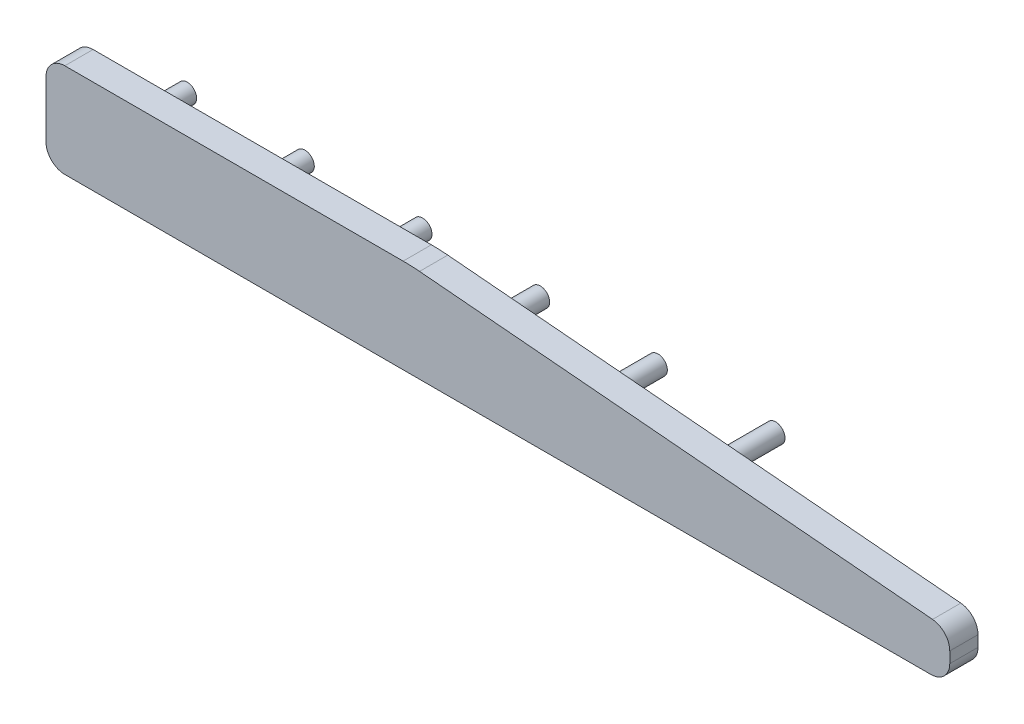
SolidWorks part; units mm, degrees
ref_plane "Front Plane" through (0, 0, 0) normal (0, 0, 1) x (1, 0, 0)
ref_plane "Top Plane" through (0, 0, 0) normal (0, 1, 0) x (1, 0, 0)
ref_plane "Right Plane" through (0, 0, 0) normal (1, 0, 0) x (0, 0, -1)
sketch "Sketch1" plane through (0, 0, 0) normal (0, 0, 1) x (1, 0, 0)
  line L1 (-50.8, 0) -> (-2387.6, 0)
  line L2 (0, 50.8) -> (0, 80.4476)
  line L3 (-1474.7904, 254) -> (-2387.6, 254)
  line L4 (-2438.4, 50.8) -> (-2438.4, 203.2)
  line L5 (-1430.5458, 252.0696) -> (-46.3755, 131.0545)
  arc A0 (0, 80.4476) -> (-46.3755, 131.0545) centre (-50.8, 80.4476) ccw
  arc A1 (-50.8, 0) -> (0, 50.8) centre (-50.8, 50.8) ccw
  arc A2 (-2387.6, 0) -> (-2438.4, 50.8) centre (-2387.6, 50.8) cw
  arc A3 (-2387.6, 254) -> (-2438.4, 203.2) centre (-2387.6, 203.2) ccw
  arc A4 (-1430.5458, 252.0696) -> (-1474.7904, 254) centre (-1474.7904, -254) ccw
  point P10 (0, 0)
  point P15 (0, 0)
  dimension "D1" = 50.8
  dimension "D2" = 508
extrude "Boss-Extrude1" add sketch "Sketch1" along normal blind 76.2
sketch "Sketch2" plane through (0, 0, 0) normal (0, 0, -1) x (-1, 0, 0)
  line L0 (2438.4, 203.2) -> (2438.4, 50.8) construction
  circle A0 centre (2286, 127) radius 25.4
  point P2 (0, 0)
  point P5 (2438.4, 127)
  dimension "D2" = 50.8
  dimension "D1" = 152.4
extrude "Boss-Extrude2" add sketch "Sketch2" along normal blind 152.4
pattern_linear "LPattern1" count 6 spacing 317.5 along (1, 0, 0) of "Boss-Extrude2"
